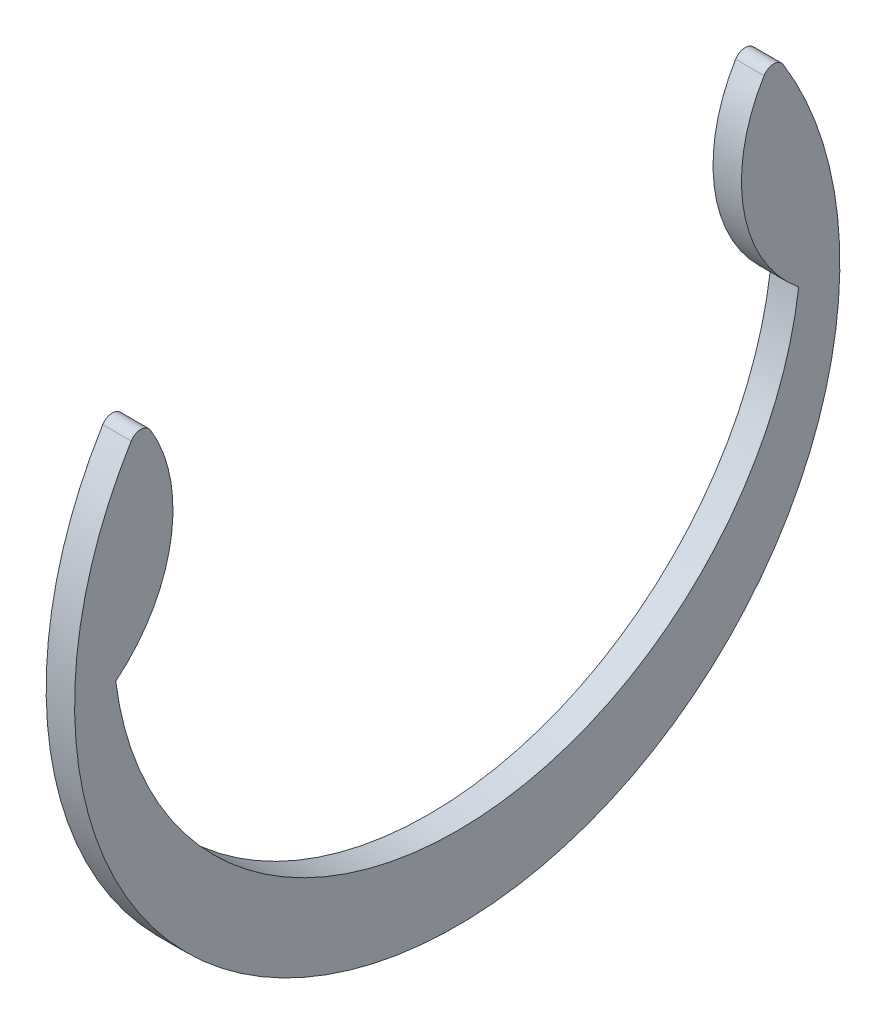
SolidWorks part; units mm, degrees
material "Steel Spring  ASTM A228 "
ref_plane "Front" through (0, 0, 0) normal (0, 0, 1) x (1, 0, 0)
ref_plane "Top" through (0, 0, 0) normal (0, 1, 0) x (1, 0, 0)
ref_plane "Right" through (0, 0, 0) normal (1, 0, 0) x (0, 0, -1)
sketch "Sketch1" plane through (0, 0, 0) normal (1, 0, 0) x (0, 0, -1)
  circle A0 centre (0, 0) radius 11.2649 construction
  arc A1 (-12.8079, 0) -> (12.8079, 0) centre (0, 1.6487) ccw
  circle A2 centre (0, 0) radius 14.351 construction
  circle A3 centre (0, 0) radius 14.605 construction
  arc A4 (12.2291, 7.5099) -> (-12.2291, 7.5099) centre (0, 0) cw
  arc A5 (-11.5074, 7.5089) -> (-12.8079, 0) centre (-16.4443, 4.4969) cw
  arc A6 (-12.2291, 7.5099) -> (-11.5074, 7.5089) centre (-11.8686, 7.2885) cw
  arc A7 (12.2291, 7.5099) -> (11.5074, 7.5089) centre (11.8686, 7.2885) ccw
  arc A8 (12.8079, 0) -> (11.5074, 7.5089) centre (16.4443, 4.4969) cw
  arc A9 (11.5074, 7.5089) -> (12.8079, 0) centre (0, 1.6487) cw construction
  dimension "A" = 22.5298
  dimension "OD" = 28.702
  dimension "D1" = 7.5099
  dimension "D2" = 25.6159
extrude "Extrude1" add sketch "Sketch1" along normal mid plane 1.0668
sketch "Sketch2" plane through (0, 0, 0) normal (0, 0, 1) x (1, 0, 0)
  line L0 (-2.921, 0) -> (8.763, 0)
  line L1 (8.763, 0) -> (8.763, -12.7)
  line L3 (8.763, -12.7) -> (0.5842, -12.7)
  line L4 (0.5842, -12.7) -> (0.5842, -11.43)
  line L5 (0.5842, -11.43) -> (-0.5842, -11.43)
  line L6 (-0.5842, -11.43) -> (-0.5842, -12.7)
  line L7 (-0.5842, -12.7) -> (-2.921, -12.7) construction
  line L8 (-2.921, -12.7) -> (-2.921, 0) construction
  line L9 (0, -11.43) -> (0, 0) construction
  line L10 (8.763, 0) -> (14.0551, 0) construction
  line L11 (-0.5842, -12.7) -> (-2.286, -12.7)
  line L12 (-2.286, -12.7) -> (-2.921, -12.065)
  line L13 (-2.921, -12.065) -> (-2.921, 0)
  point P14 (-0.5842, -12.065)
  dimension "D2" = 11.684
  dimension "D3" = 2.921
  dimension "D4" = 45
revolve "Revolve1" [suppressed] add sketch "Sketch2" angle 360 about L10
equation "\"D2@Sketch2\" = \"W@Sketch2\"*10"
equation "\"D3@Sketch2\" = \"D2@Sketch2\"/4"
equation "\"D1@Sketch1\" = \"A@Sketch1\"/3"
equation "\"D2@Sketch1\" = (\"OD@Sketch1\"+\"A@Sketch1\")/2"
